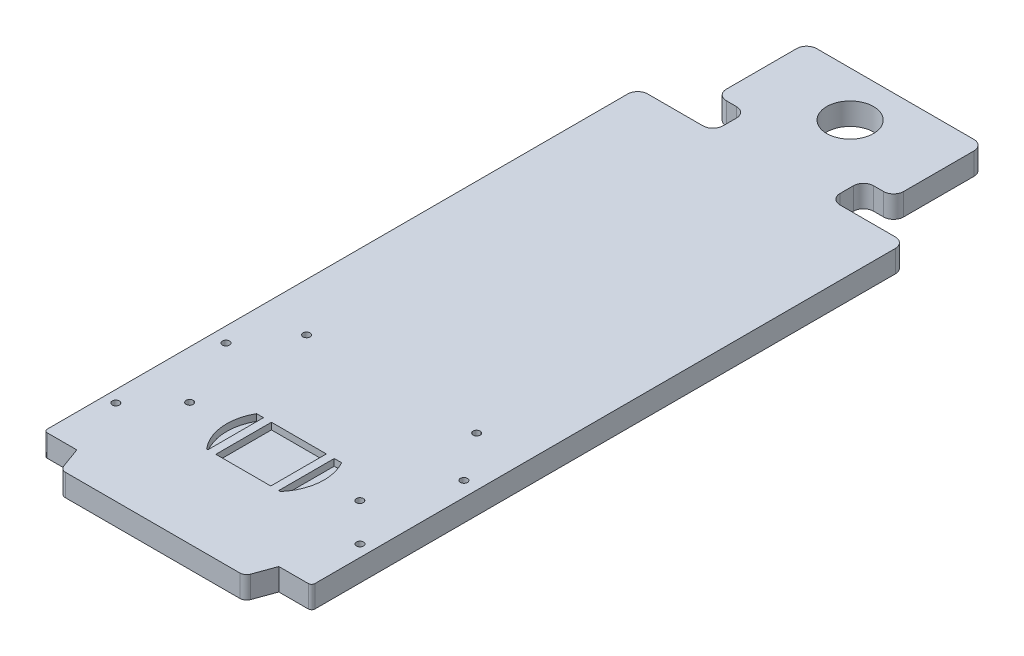
SolidWorks part; units mm, degrees
ref_plane "Front Plane" through (0, 0, 0) normal (0, 0, 1) x (1, 0, 0)
ref_plane "Top Plane" through (0, 0, 0) normal (0, 1, 0) x (1, 0, 0)
ref_plane "Right Plane" through (0, 0, 0) normal (1, 0, 0) x (0, 0, -1)
sketch "Sketch1" plane through (0, 0, 0) normal (0, 1, 0) x (1, 0, 0)
  line L0 (13.918, 220.8997) -> (13.918, -51.5153) construction
  line L1 (-15.927, 220.8997) -> (43.763, 220.8997)
  line L2 (-19.737, 217.0897) -> (-19.737, 190.4197)
  line L3 (-36.882, -51.5153) -> (-24.436, -51.5153)
  line L4 (47.573, 217.0897) -> (47.573, 190.4197)
  line L5 (-15.927, 186.6097) -> (-12.117, 186.6097)
  line L6 (64.718, 170.0997) -> (64.718, -51.5153)
  line L7 (-33.072, 173.9097) -> (-12.117, 173.9097)
  line L8 (-8.307, 182.7997) -> (-8.307, 177.7197)
  line L9 (43.763, 186.6097) -> (39.953, 186.6097)
  line L10 (60.908, 173.9097) -> (39.953, 173.9097)
  line L11 (36.143, 182.7997) -> (36.143, 177.7197)
  line L12 (-36.882, 170.0997) -> (-36.882, -51.5153)
  line L13 (52.272, -51.5153) -> (64.718, -51.5153)
  line L14 (-24.436, -51.5153) -> (-21.5775, -59.369)
  line L15 (-24.436, -51.5153) -> (-24.436, -61.0403) construction
  line L16 (-24.436, -61.0403) -> (52.272, -61.0403) construction
  line L17 (52.272, -51.5153) -> (52.272, -61.0403) construction
  line L18 (-19.1907, -61.0403) -> (47.0267, -61.0403)
  line L19 (49.4135, -59.369) -> (52.272, -51.5153)
  line L20 (-36.882, -13.4153) -> (64.718, -13.4153) construction
  line L30 (-19.737, 203.7547) -> (13.918, 203.7547) construction
  circle A0 centre (13.918, 203.7547) radius 8.89
  arc A1 (47.0267, -61.0403) -> (49.4135, -59.369) centre (47.0267, -58.5003) ccw
  arc A2 (-21.5775, -59.369) -> (-19.1907, -61.0403) centre (-19.1907, -58.5003) ccw
  arc A3 (-15.927, 220.8997) -> (-19.737, 217.0897) centre (-15.927, 217.0897) ccw
  arc A4 (43.763, 220.8997) -> (47.573, 217.0897) centre (43.763, 217.0897) cw
  arc A5 (43.763, 186.6097) -> (47.573, 190.4197) centre (43.763, 190.4197) ccw
  arc A6 (60.908, 173.9097) -> (64.718, 170.0997) centre (60.908, 170.0997) cw
  arc A7 (39.953, 173.9097) -> (36.143, 177.7197) centre (39.953, 177.7197) cw
  arc A8 (39.953, 186.6097) -> (36.143, 182.7997) centre (39.953, 182.7997) ccw
  arc A9 (-15.927, 186.6097) -> (-19.737, 190.4197) centre (-15.927, 190.4197) cw
  arc A10 (-12.117, 186.6097) -> (-8.307, 182.7997) centre (-12.117, 182.7997) cw
  arc A11 (-12.117, 173.9097) -> (-8.307, 177.7197) centre (-12.117, 177.7197) ccw
  arc A12 (-36.882, 170.0997) -> (-33.072, 173.9097) centre (-33.072, 170.0997) cw
  point P24 (48.8052, -61.0403)
  point P27 (-20.9692, -61.0403)
  point P34 (47.573, 186.6097)
  point P37 (64.718, 173.9097)
  point P40 (36.143, 173.9097)
  point P43 (36.143, 186.6097)
  point P46 (-19.737, 186.6097)
  point P49 (-8.307, 186.6097)
  point P52 (-8.307, 173.9097)
  point P55 (-36.882, 173.9097)
  dimension "D6" = 17.78
  dimension "D12" = 2.54
  dimension "D13" = 3.81
  dimension "D1" = 225.425
  dimension "D2" = 12.7
  dimension "D3" = 33.655
  dimension "D4" = 34.29
  dimension "D5" = 101.6
  dimension "D7" = 12.446
  dimension "D8" = 12.446
  dimension "D9" = 9.525
  dimension "D10" = 20
  dimension "D11" = 20
  dimension "D14" = 38.1
extrude "Boss-Extrude1" add sketch "Sketch1" along normal blind 8.382
fillet "Fillet3" radius 1.27 2 edges at (64.718, 4.191, 51.5153) (-36.882, 4.191, 51.5153)
sketch "Sketch2" plane through (0, 8.382, 0) normal (0, 1, 0) x (1, 0, 0)
  line L0 (13.918, -26.5703) -> (-0.0763, -26.5703)
  line L1 (-0.0763, -26.5703) -> (27.9123, -26.5703)
  line L2 (13.918, -32.9703) -> (13.918, -26.5703)
  line L3 (13.918, 4.0297) -> (13.918, -5.4703)
  line L5 (-2.2452, -5.4703) -> (30.0812, -5.4703)
  line L11 (0.4137, -5.4703) -> (3.4137, -5.4703)
  line L12 (0.4137, -5.4703) -> (0.4137, -26.5703)
  line L13 (0.4137, -26.5703) -> (3.4137, -26.5703)
  line L14 (3.4137, -5.4703) -> (3.4137, -26.5703)
  line L15 (27.2661, -5.4703) -> (24.2661, -5.4703)
  line L16 (27.2661, -5.4703) -> (27.2661, -26.5703)
  line L17 (27.2661, -26.5703) -> (24.2661, -26.5703)
  line L18 (24.2661, -5.4703) -> (24.2661, -26.5703)
  circle A0 centre (13.918, -14.4703) radius 18.5
  point P8 (24.2661, -26.5703)
  point P11 (3.4137, -26.5703)
  dimension "D1" = 3
  dimension "D2" = 3
sketch "Sketch4" plane through (0, 8.382, 0) normal (0, 1, 0) x (1, 0, 0)
  line L1 (13.918, -14.4703) -> (-18.627, -14.4703)
  circle A2 centre (13.918, -14.4703) radius 13.11
hole_wizard "Tap Drill for #6-32 Tap2" positions "Sketch8" profile "Sketch9" hole size "#6-32" standard "ANSI Inch" end condition through all
sketch "Sketch8" plane through (0, 8.382, 0) normal (0, 1, 0) x (1, 0, 0)
  point P0 (-18.627, -14.4703)
sketch "Sketch9" plane through (-18.627, 8.382, 14.4703) normal (1, 0, 0) x (0, 0, 1)
  line L0 (0, 0) -> (0, 8.382)
  line L1 (0, 8.382) -> (1.3525, 8.382)
  line L2 (1.3525, 8.382) -> (1.3525, 0)
  line L5 (1.3525, 0) -> (0, 0)
  line L11 (0, -6.35) -> (0, 107.95) construction
  dimension "Thru Hole Dia." = 2.7051
  dimension "Thru Hole Depth" = 8.382
pattern_linear "LPattern1" count 2 spacing 44.39 along (0, 0, -1) count 2 spacing 64.59 along (1, 0, 0) of "Tap Drill for #6-32 Tap2"
sketch "Sketch10" plane through (0, 8.382, 0) normal (0, 1, 0) x (1, 0, 0)
  line L0 (-36.882, 11.9247) -> (-31.252, 11.9247)
  line L3 (64.718, 11.9247) -> (59.088, 11.9247)
  line L5 (-36.882, 170.0997) -> (-36.882, -50.2453) construction
  line L6 (64.718, -50.2453) -> (64.718, 170.0997) construction
hole_wizard "Tap Drill for #6-32 Tap3" positions "Sketch13" profile "Sketch14" hole size "#6-32" standard "ANSI Inch" end condition through all
sketch "Sketch13" plane through (0, 8.382, 0) normal (0, 1, 0) x (1, 0, 0)
  point P0 (-31.252, 11.9247)
  point P3 (59.088, 11.9247)
sketch "Sketch14" plane through (-31.252, 8.382, -11.9247) normal (1, 0, 0) x (0, 0, 1)
  line L0 (0, 0) -> (0, 8.382)
  line L1 (0, 8.382) -> (1.3525, 8.382)
  line L2 (1.3525, 8.382) -> (1.3525, 0)
  line L5 (1.3525, 0) -> (0, 0)
  line L11 (0, -6.35) -> (0, 107.95) construction
  dimension "Thru Hole Dia." = 2.7051
  dimension "Thru Hole Depth" = 8.382
sketch "Sketch15" plane through (0, 8.382, 0) normal (0, 1, 0) x (1, 0, 0)
  line L0 (13.918, -23.4703) -> (13.918, -28.7003)
  line L2 (-36.882, 170.0997) -> (-36.882, -50.2453) construction
  line L4 (64.718, -50.2453) -> (64.718, 170.0997) construction
  line L5 (-36.882, -28.7003) -> (-32.452, -28.7003)
  line L6 (64.718, -28.7003) -> (60.288, -28.7003)
  circle A1 centre (13.918, -14.4703) radius 9
hole_wizard "Tap Drill for #6-32 Tap5" positions "Sketch18" profile "Sketch19" hole size "#6-32" standard "ANSI Inch" end condition through all
sketch "Sketch18" plane through (0, 8.382, 0) normal (0, 1, 0) x (1, 0, 0)
  point P0 (-32.452, -28.7003)
  point P3 (60.288, -28.7003)
sketch "Sketch19" plane through (-32.452, 8.382, 28.7003) normal (1, 0, 0) x (0, 0, 1)
  line L0 (0, 0) -> (0, 8.382)
  line L1 (0, 8.382) -> (1.3525, 8.382)
  line L2 (1.3525, 8.382) -> (1.3525, 0)
  line L5 (1.3525, 0) -> (0, 0)
  line L11 (0, -6.35) -> (0, 107.95) construction
  dimension "Thru Hole Dia." = 2.7051
  dimension "Thru Hole Depth" = 8.382
extrude "Cut-Extrude2" cut sketch "Sketch2" against normal blind 2.54 and the other way through all contours L5 A0 L1 L12 | L18 L5 L14 L0 L1 | L1 A0 L5 L16
